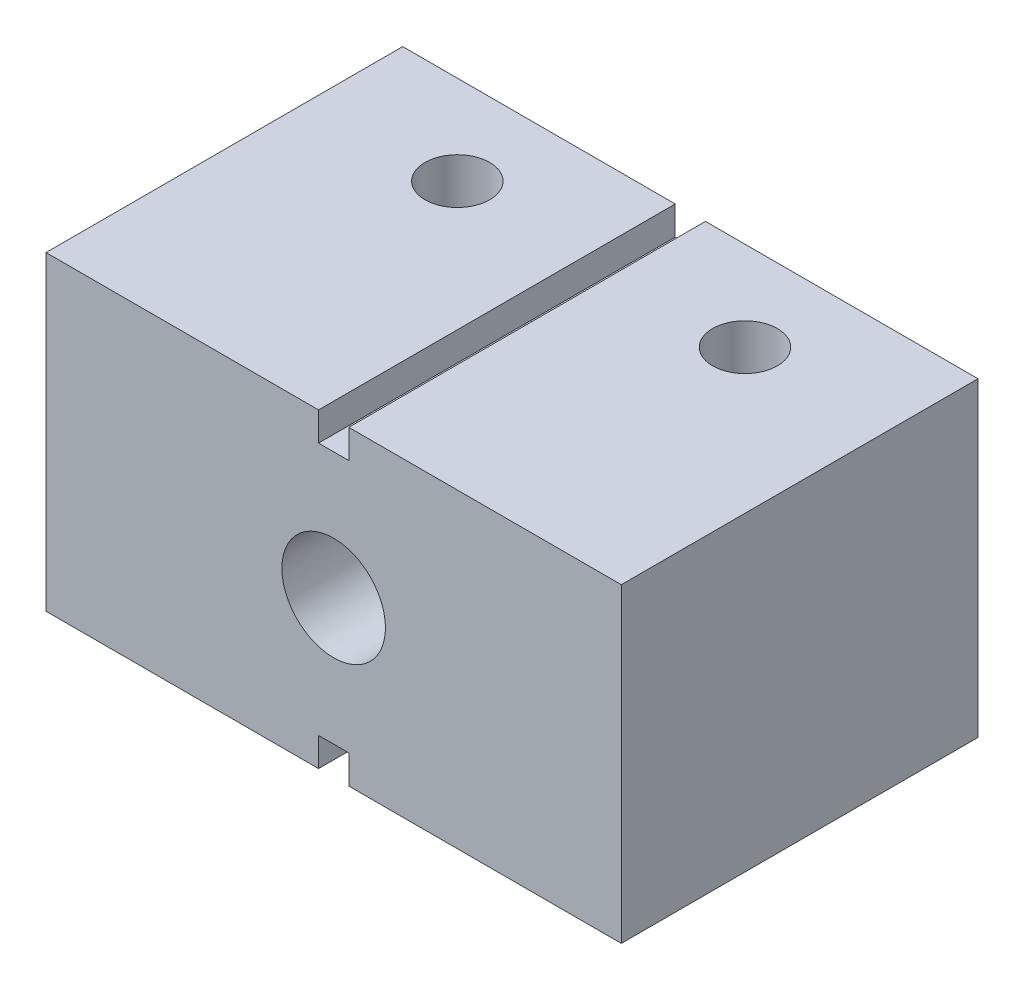
SolidWorks part; units mm, degrees
ref_plane "Front Plane" through (0, 0, 0) normal (0, 0, 1) x (1, 0, 0)
ref_plane "Top Plane" through (0, 0, 0) normal (0, 1, 0) x (1, 0, 0)
ref_plane "Right Plane" through (0, 0, 0) normal (1, 0, 0) x (0, 0, -1)
sketch "Sketch1" plane through (0, 0, 0) normal (0, 0, 1) x (1, 0, 0)
  line L1 (-20, 10.8) -> (20, 10.8)
  line L2 (-20, 10.8) -> (-20, -10.8)
  line L3 (-20, -10.8) -> (20, -10.8)
  line L4 (20, 10.8) -> (20, -10.8)
  line L5 (-20, 10.8) -> (20, -10.8) construction
  line L6 (-20, -10.8) -> (20, 10.8) construction
  circle A0 centre (0, 0) radius 3.6
  point P0 (0, 0)
  dimension "D3" = 7.2
  dimension "D1" = 21.6
  dimension "D2" = 40
extrude "Boss-Extrude1" add sketch "Sketch1" along normal blind 24.8
sketch "Sketch2" plane through (0, 10.8, 0) normal (0, 1, 0) x (1, 0, 0)
  line L0 (0, -24.8) -> (0, 0) construction
  line L1 (20, -24.8) -> (-20, -24.8) construction
  line L2 (0, 0) -> (-20, 0) construction
  line L3 (-20, 0) -> (0, -12.4) construction
  line L4 (0, -12.4) -> (20, 0) construction
  circle A0 centre (-10, -6.2) radius 2.25
  circle A1 centre (10, -6.2) radius 2.25
  dimension "D1" = 4.5
extrude "Cut-Extrude1" cut sketch "Sketch2" against normal up to next
sketch "Sketch3" plane through (0, 10.8, 0) normal (0, 1, 0) x (1, 0, 0)
  line L0 (20, -24.8) -> (-20, -24.8) construction
  line L1 (-1.05, -24.8) -> (1.05, -24.8)
  line L2 (-1.05, -24.8) -> (-1.05, 0)
  line L3 (-1.05, 0) -> (1.05, 0)
  line L4 (1.05, -24.8) -> (1.05, 0)
  line L5 (-1.05, -24.8) -> (1.05, 0) construction
  line L6 (-1.05, 0) -> (1.05, -24.8) construction
  line L7 (20, 0) -> (-20, 0) construction
  point P0 (0, -12.4)
  point P7 (0, -24.8)
  point P8 (0, -24.8)
  point P11 (0, 0)
  point P12 (0, 0)
  dimension "D1" = 2.1
extrude "Cut-Extrude2" cut sketch "Sketch3" against normal blind 2
sketch "Sketch4" plane through (0, -10.8, 0) normal (0, -1, 0) x (1, 0, 0)
  line L4 (1.05, 0) -> (1.05, 24.8)
  line L5 (-1.05, 0) -> (1.05, 0)
  line L6 (-1.05, 24.8) -> (-1.05, 0)
  line L7 (1.05, 24.8) -> (-1.05, 24.8)
  line L8 (1.05, 0) -> (1.05, 24.8)
  line L9 (-1.05, 0) -> (1.05, 0)
  line L10 (-1.05, 24.8) -> (-1.05, 0)
  line L11 (1.05, 24.8) -> (-1.05, 24.8)
  dimension "D1" = 0
extrude "Cut-Extrude3" cut sketch "Sketch4" against normal blind 2
sketch "Sketch5" plane through (0, 0, 0) normal (0, 0, -1) x (-1, 0, 0)
  line L0 (-8.2967, -10.8) -> (-8.2967, 10.8) construction
  line L1 (-20, 10.8) -> (-1.05, 10.8) construction
  line L2 (-1.05, -10.8) -> (-20, -10.8) construction
  text T0 "18 mm" font "Century Gothic" height 3.5
  point P4 (0, 0)
extrude "Cut-Extrude4" cut sketch "Sketch5" against normal blind 1.2
